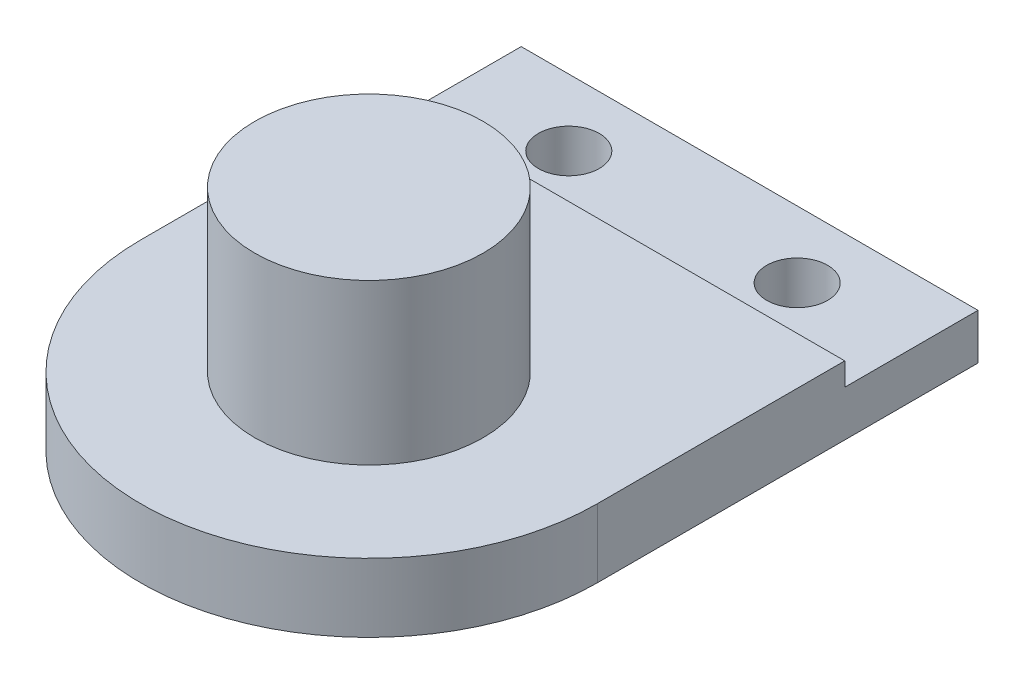
SolidWorks part; units mm, degrees
ref_plane "Front Plane" through (0, 0, 0) normal (0, 0, 1) x (1, 0, 0)
ref_plane "Top Plane" through (0, 0, 0) normal (0, 1, 0) x (1, 0, 0)
ref_plane "Right Plane" through (0, 0, 0) normal (1, 0, 0) x (0, 0, -1)
sketch "Sketch1" plane through (0, 0, 0) normal (0, 1, 0) x (1, 0, 0)
  line L1 (-3.4655, 4.7414) -> (8.5345, 4.7414)
  line L2 (-3.4655, 4.7414) -> (-3.4655, -5.2586)
  line L4 (8.5345, 4.7414) -> (8.5345, -5.2586)
  arc A0 (-3.4655, -5.2586) -> (8.5345, -5.2586) centre (2.5345, -5.2586) ccw
  dimension "D1" = 10
  dimension "D2" = 12
extrude "Boss-Extrude1" add sketch "Sketch1" along normal blind 1.8
sketch "Sketch2" plane through (0, 1.8, 0) normal (0, 1, 0) x (1, 0, 0)
  line L0 (8.5345, -5.2586) -> (8.5345, 4.7414) construction
  line L1 (-3.4655, 4.7414) -> (8.5345, 4.7414)
  line L2 (-3.4655, 4.7414) -> (-3.4655, 1.2414)
  line L3 (-3.4655, 1.2414) -> (8.5345, 1.2414)
  line L4 (8.5345, 4.7414) -> (8.5345, 1.2414)
  dimension "D1" = 3.5
extrude "Cut-Extrude1" cut sketch "Sketch2" against normal blind 0.6
sketch "Sketch3" plane through (0, 1.8, 0) normal (0, 1, 0) x (1, 0, 0)
  circle A0 centre (2.5345, -5.2586) radius 3
extrude "Boss-Extrude2" add sketch "Sketch3" along normal blind 4.2
sketch "Sketch4" plane through (0, 1.2, 0) normal (0, 1, 0) x (1, 0, 0)
  line L0 (8.5345, 1.2414) -> (8.5345, 4.7414) construction
  line L2 (8.5345, 4.7414) -> (-3.4655, 4.7414) construction
  line L3 (2.5345, -5.2586) -> (2.5345, 4.7414) construction
  circle A0 centre (5.5345, 2.9914) radius 0.8
  circle A1 centre (-0.4655, 2.9914) radius 0.8
  dimension "D1" = 3
  dimension "D2" = 1.75
extrude "Cut-Extrude2" cut sketch "Sketch4" against normal through all
